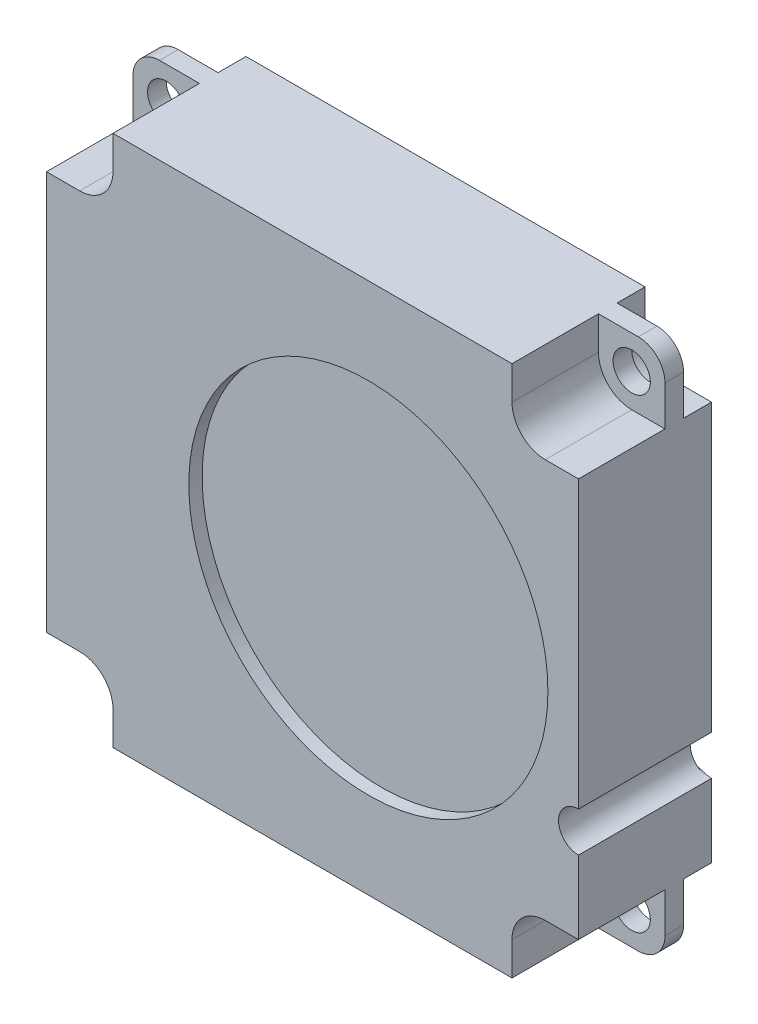
SolidWorks part; units mm, degrees
material "ABS"
ref_plane "Спереди" through (0, 0, 0) normal (0, 0, 1) x (1, 0, 0)
ref_plane "Сверху" through (0, 0, 0) normal (0, 1, 0) x (1, 0, 0)
ref_plane "Справа" through (0, 0, 0) normal (1, 0, 0) x (0, 0, -1)
other "Configuration Table"
sketch "Эскиз1" plane through (0, 0, 0) normal (0, 0, 1) x (1, 0, 0)
  line L1 (0, 0) -> (40, 0)
  line L2 (0, 0) -> (0, 40)
  line L3 (0, 40) -> (40, 40)
  line L4 (40, 0) -> (40, 40)
  dimension "D1" = 40
extrude "Бобышка-Вытянуть1" add sketch "Эскиз1" along normal blind 10
sketch "Эскиз2" plane through (0, 0, 10) normal (0, 0, 1) x (1, 0, 0)
  line L8 (2.5, 37.5) -> (2.5, 2.5)
  line L9 (2.5, 2.5) -> (37.5, 2.5)
  line L10 (37.5, 2.5) -> (37.5, 37.5)
  line L11 (37.5, 37.5) -> (2.5, 37.5)
  line L12 (2.5, 37.5) -> (2.5, 2.5) construction
  line L13 (2.5, 2.5) -> (37.5, 2.5) construction
  line L14 (37.5, 2.5) -> (37.5, 37.5) construction
  line L15 (37.5, 37.5) -> (2.5, 37.5) construction
  circle A0 centre (2.5, 37.5) radius 1.4
  circle A1 centre (37.5, 37.5) radius 1.4
  circle A2 centre (37.5, 2.5) radius 1.4
  circle A3 centre (2.5, 2.5) radius 1.4
  dimension "D2" = 2.8
  dimension "D1" = 2.5
extrude "Вырез-Вытянуть1" cut sketch "Эскиз2" against normal through all
sketch "Эскиз3" plane through (0, 0, 10) normal (0, 0, 1) x (1, 0, 0)
  line L0 (0, 0) -> (40, 0) construction
  line L1 (40, 0) -> (40, 40) construction
  circle A0 centre (24.2, 20) radius 13.5
  dimension "D1" = 27
  dimension "D2" = 20
  dimension "D3" = 15.8
extrude "Вырез-Вытянуть2" cut sketch "Эскиз3" against normal blind 1
sketch "Эскиз4" plane through (0, 0, 0) normal (0, -1, 0) x (1, 0, 0)
  line L0 (6, 9.3) -> (6, 0.7)
  line L1 (6, 0.7) -> (34, 0.7)
  line L2 (34, 0.7) -> (34, 9.3)
  line L3 (34, 9.3) -> (6, 9.3)
  line L4 (0, 10) -> (40, 10) construction
  line L5 (40, 10) -> (40, 0) construction
  point P6 (20, 10)
  point P7 (20, 9.3)
  point P10 (40, 5)
  point P11 (34, 5)
  dimension "D1" = 28
  dimension "D2" = 8.6
extrude "Вырез-Вытянуть3" cut sketch "Эскиз4" against normal blind 5
sketch "Эскиз5" plane through (0, 0, 10) normal (0, 0, 1) x (1, 0, 0)
  line L0 (2.5, 35) -> (0, 35)
  line L1 (0, 40) -> (0, 0) construction
  line L2 (0, 35) -> (0, 40)
  line L3 (0, 40) -> (5, 40)
  line L4 (40, 40) -> (0, 40) construction
  line L5 (5, 40) -> (5, 37.5)
  line L6 (20, 40) -> (20, 0) construction
  line L7 (0, 0) -> (40, 0) construction
  line L8 (0, 20) -> (40, 20) construction
  line L9 (40, 0) -> (40, 40) construction
  line L10 (35, 40) -> (35, 37.5)
  line L11 (40, 40) -> (35, 40)
  line L12 (40, 35) -> (40, 40)
  line L13 (37.5, 35) -> (40, 35)
  line L14 (37.5, 5) -> (40, 5)
  line L15 (40, 5) -> (40, 0)
  line L16 (40, 0) -> (35, 0)
  line L17 (35, 0) -> (35, 2.5)
  line L18 (5, 0) -> (5, 2.5)
  line L19 (0, 0) -> (5, 0)
  line L20 (0, 5) -> (0, 0)
  line L21 (2.5, 5) -> (0, 5)
  arc A0 (2.5, 35) -> (5, 37.5) centre (2.5, 37.5) ccw
  arc A1 (37.5, 35) -> (35, 37.5) centre (37.5, 37.5) cw
  arc A2 (37.5, 5) -> (35, 2.5) centre (37.5, 2.5) ccw
  arc A3 (2.5, 5) -> (5, 2.5) centre (2.5, 2.5) cw
extrude "Вырез-Вытянуть4" cut sketch "Эскиз5" against normal blind 6.5
sketch "Эскиз6" plane through (0, 0, 0) normal (0, 0, -1) x (-1, 0, 0)
  line L4 (-2.5, 35) -> (0, 35)
  line L5 (0, 35) -> (0, 40)
  line L6 (0, 40) -> (-5, 40)
  line L7 (-5, 40) -> (-5, 37.5)
  line L8 (-2.5, 35) -> (0, 35)
  line L9 (0, 35) -> (0, 40)
  line L10 (0, 40) -> (-5, 40)
  line L11 (-5, 40) -> (-5, 37.5)
  line L12 (-35, 37.5) -> (-35, 40)
  line L13 (-40, 35) -> (-37.5, 35)
  line L14 (-40, 40) -> (-40, 35)
  line L15 (-35, 40) -> (-40, 40)
  line L16 (-35, 37.5) -> (-35, 40)
  line L17 (-40, 35) -> (-37.5, 35)
  line L18 (-40, 40) -> (-40, 35)
  line L19 (-35, 40) -> (-40, 40)
  line L20 (-5, 0) -> (0, 0)
  line L21 (0, 0) -> (0, 5)
  line L22 (0, 5) -> (-2.5, 5)
  line L23 (-5, 2.5) -> (-5, 0)
  line L24 (-5, 0) -> (0, 0)
  line L25 (0, 0) -> (0, 5)
  line L26 (0, 5) -> (-2.5, 5)
  line L27 (-5, 2.5) -> (-5, 0)
  line L28 (-40, 5) -> (-40, 0)
  line L29 (-40, 0) -> (-35, 0)
  line L30 (-35, 0) -> (-35, 2.5)
  line L31 (-37.5, 5) -> (-40, 5)
  line L32 (-40, 5) -> (-40, 0)
  line L33 (-40, 0) -> (-35, 0)
  line L34 (-35, 0) -> (-35, 2.5)
  line L35 (-37.5, 5) -> (-40, 5)
  arc A1 (-5, 37.5) -> (-2.5, 35) centre (-2.5, 37.5) ccw
  arc A2 (-5, 37.5) -> (-2.5, 35) centre (-2.5, 37.5) ccw
  arc A3 (-37.5, 35) -> (-35, 37.5) centre (-37.5, 37.5) ccw
  arc A4 (-37.5, 35) -> (-35, 37.5) centre (-37.5, 37.5) ccw
  arc A5 (-2.5, 5) -> (-5, 2.5) centre (-2.5, 2.5) ccw
  arc A6 (-2.5, 5) -> (-5, 2.5) centre (-2.5, 2.5) ccw
  arc A7 (-35, 2.5) -> (-37.5, 5) centre (-37.5, 2.5) ccw
  arc A8 (-35, 2.5) -> (-37.5, 5) centre (-37.5, 2.5) ccw
  dimension "D1" = 0
  dimension "D2" = 0
  dimension "D3" = 0
  dimension "D4" = 0
extrude "Вырез-Вытянуть5" cut sketch "Эскиз6" against normal blind 2.1
fillet "Скругление2" radius 2 4 edges at (40, 0, 2.8) (0, 0, 2.8) (40, 40, 2.8) (0, 40, 2.8)
sketch "Эскиз8" plane through (0, 0, 10) normal (0, 0, 1) x (1, 0, 0)
  line L0 (40, 5) -> (40, 35) construction
  line L1 (5, 0) -> (35, 0) construction
  circle A0 centre (40, 12) radius 1.5
  dimension "D2" = 3
  dimension "D1" = 12
extrude "Вырез-Вытянуть6" cut sketch "Эскиз8" against normal through all
sketch "Эскиз9" plane through (0, 0, 0) normal (0, 0, -1) x (-1, 0, 0)
  line L0 (-35, 40) -> (-5, 40) construction
  line L1 (0, 35) -> (0, 5) construction
  line L2 (-40, 13.5) -> (-33.3145, 15.6728)
  line L4 (-39.5364, 10.5734) -> (-32.1158, 12.9851)
  arc A0 (-32.1158, 12.9851) -> (-33.3145, 15.6728) centre (-20, 20) ccw
  arc A1 (-40, 10.5) -> (-40, 13.5) centre (-40, 12) ccw construction
  arc A2 (-39.5364, 10.5734) -> (-40, 13.5) centre (-40, 12) ccw
  point P4 (-20, 40)
  point P7 (0, 20)
  dimension "D1" = 28
extrude "Вырез-Вытянуть7" cut sketch "Эскиз9" against normal blind 0.1
sketch "Sketch1" plane through (0, 0, 10) normal (0, 0, 1) x (1, 0, 0)
  line L0 (5, 0) -> (35, 0)
sketch "Sketch2" plane through (0, 0, 0) normal (0, 0, -1) x (-1, 0, 0)
  line L0 (-5, 0) -> (-35, 0)
